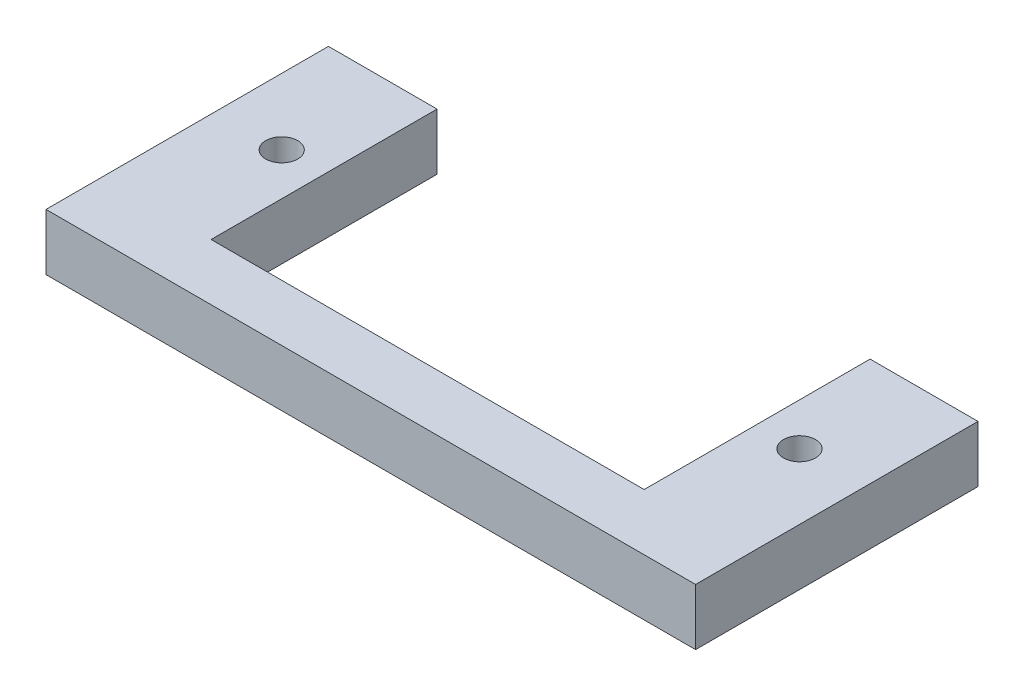
SolidWorks part; units mm, degrees
ref_plane "前视基准面" through (0, 0, 0) normal (0, 0, 1) x (1, 0, 0)
ref_plane "上视基准面" through (0, 0, 0) normal (0, 1, 0) x (1, 0, 0)
ref_plane "右视基准面" through (0, 0, 0) normal (1, 0, 0) x (0, 0, -1)
other "Configuration Table"
sketch "草图1" plane through (0, 0, 0) normal (0, 1, 0) x (1, 0, 0)
  line L0 (-46.3412, 15) -> (-46.3412, 0)
  line L1 (-46.3412, 0) -> (-11.8412, 0)
  line L2 (-11.8412, 0) -> (-11.8412, 15)
  line L3 (-11.8412, 15) -> (-17.572, 15)
  line L4 (-17.572, 15) -> (-17.572, 3)
  line L5 (-17.572, 3) -> (-40.572, 3)
  line L6 (-40.572, 3) -> (-40.572, 15)
  line L7 (-40.572, 15) -> (-46.3412, 15)
  line L8 (-42.822, 15) -> (-42.822, 9) construction
  line L9 (-40.572, 9) -> (-42.822, 9) construction
  line L10 (-29.072, 3) -> (-29.072, 18.8151) construction
  circle A0 centre (-42.822, 9) radius 0.85
  circle A1 centre (-15.322, 9) radius 0.85
extrude "凸台-拉伸1" add sketch "草图1" along normal blind 3
